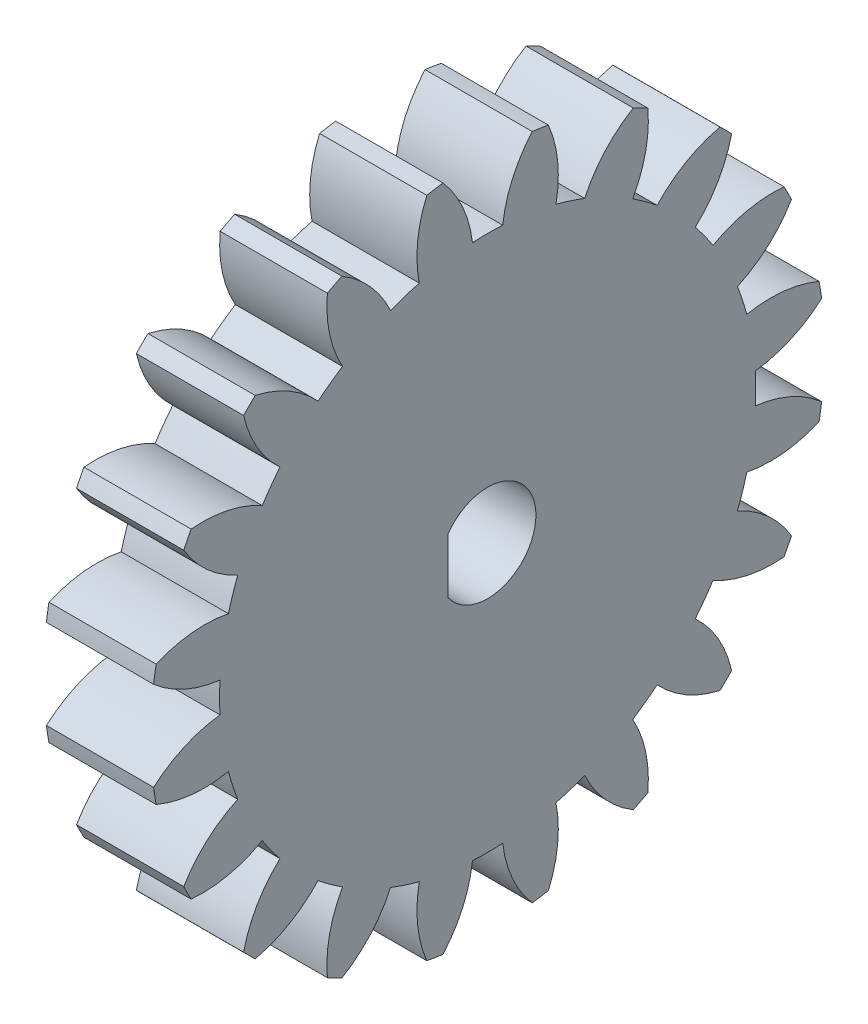
SolidWorks part; units mm, degrees
ref_plane "Plane1" through (0, 0, 0) normal (0, 0, 1) x (1, 0, 0)
ref_plane "Plane2" through (0, 0, 0) normal (0, 1, 0) x (1, 0, 0)
ref_plane "Plane3" through (0, 0, 0) normal (1, 0, 0) x (0, 0, -1)
other "Configuration Table"
sketch "HoldingSke" plane through (0, 0, 0) normal (0, 1, 0) x (1, 0, 0)
  line L0 (0, 0) -> (0.4698, -0.171)
  line L1 (-15, 0) -> (100, 0) construction
  line L2 (0, 0) -> (-2.1039, 2.3779)
  line L3 (0, 0) -> (-11.863, 4.5341)
  line L4 (0, 0) -> (8.1152, 2.9537)
  line L5 (0, 0) -> (-12.1804, -4.5429)
  line L6 (0, 0) -> (-5.8027, -3.9151)
  line L7 (-2.1039, 2.3779) -> (0.6944, 15.0732)
  line L8 (-76.2, 54.61) -> (-75.2, 54.61)
  line L9 (-71.009, 38.7566) -> (-53.1078, 45.2721)
  line L10 (-76.2, 71.12) -> (104.1128, 71.12)
  line L11 (0, 0) -> (-7, 0)
  line L12 (-76.2, 101.6) -> (-76.133, 101.6)
  line L13 (24.9733, 27.94) -> (52.9518, 28.4284)
  line L14 (24.9733, 27.94) -> (24.9743, 27.94)
  line L15 (24.9733, 27.94) -> (100.4006, 29.5858)
  line L16 (-63.627, -2) -> (-12.827, -2)
  circle A0 centre (0, 0) radius 3
  circle A1 centre (0, 0) radius 5
  circle A2 centre (0, 0) radius 5
  circle A3 centre (0, 0) radius 3
  dimension "MHD" = 10
  dimension "Hub_dia" = 10
  dimension "Bore" = 6
  dimension "MBD" = 6
  dimension "Num_teeth" = 20
  dimension "Pitch" = 0.5
  dimension "Overall_len" = 13
  dimension "Show_teeth" = 20
  dimension "Thickness" = 7
  dimension "OAL" = 13.0001
  dimension "T_dim" = 1
  dimension "Ap" = 20
  dimension "H" = 19.05
  dimension "Pitch_radius" = 180.3128
  dimension "Width" = 7
  dimension "Backlash" = 0.067
  dimension "Addendum_fac" = 1
  dimension "Dedendum_fac" = 1.25
  dimension "Clearance_fac" = 0.25
  dimension "Dedendum_add" = 0.001
  dimension "Module" = 2
sketch "BasProSke" plane through (0, 0, 0) normal (0, 1, 0) x (1, 0, 0)
  line L0 (-10, 0) -> (60, 0) construction
  line L1 (0, 0) -> (0, 22)
  line L2 (0, 0) -> (7, 0)
  line L3 (7, 0) -> (7, 22)
  line L4 (7, 22) -> (0, 22)
  dimension "Thickness" = 7
  dimension "Diameter" = 44
revolve "Base-Revolve" add sketch "BasProSke" angle 360 about L0
sketch "TooCutSke" plane through (0, 0, 0) normal (1, 0, 0) x (0, 0, -1)
  line L1 (0, 0) -> (0, 107) construction
  line L2 (0, 0) -> (-1.6864, 19.9288) construction
  line L3 (0, 0) -> (-6.2409, 39.4033) construction
  line L4 (-1.6864, 19.9288) -> (-3.1204, 19.7016) construction
  arc A0 (0.9862, 17.4712) -> (-0.9862, 17.4712) centre (0, 0) ccw
  arc A1 (2.9329, 21.8293) -> (-2.9329, 21.8293) centre (0, 0) ccw
  circle A2 centre (0, 0) radius 20 construction
  circle A3 centre (0, 0) radius 18.7939 construction
  arc A4 (-0.9862, 17.4712) -> (-2.9329, 21.8293) centre (-8.9313, 16.536) ccw
  arc A5 (2.9329, 21.8293) -> (0.9862, 17.4712) centre (8.9313, 16.536) ccw
  dimension "Root_dia" = 34.998
  dimension "Overcut_dia" = 44.0508
  dimension "Pitch_dia" = 40
  dimension "Base_dia" = 37.5877
  dimension "Flank_rad" = 8
  dimension "Half_ang" = 9
  dimension "Half_CT" = 1.4519
extrude "ToothCut" cut sketch "TooCutSke" along normal through all
fillet "Breaks" [suppressed] radius 0.04
fillet "RootFillets" [suppressed] radius 0.501
pattern_circular "TeethCuts" count 20 every 18 about axis through (-10, 0, 0) along (1, 0, 0) of "ToothCut", "RootFillets", "Breaks"
sketch "HubNeaOneSke" plane through (0, 0, 0) normal (-1, 0, 0) x (0, 0, 1)
  circle A0 centre (0, 0) radius 7
  dimension "Diameter" = 14
extrude "HubNearOne" add sketch "HubNeaOneSke" along normal blind 6.0001
sketch "HubNeaBotSke" plane through (0, 0, 0) normal (-1, 0, 0) x (0, 0, 1)
  circle A0 centre (0, 0) radius 5
  dimension "Diameter" = 10
extrude "HubNearBoth" [suppressed] add sketch "HubNeaBotSke" along normal blind 3
ref_plane "FarPln" through (7, 0, 0) normal (1, 0, 0) x (0, 0, -1)
sketch "HubFarSke" plane through (7, 0, 0) normal (1, 0, 0) x (0, 0, -1)
  circle A0 centre (0, 0) radius 5
  dimension "Diameter" = 10
extrude "HubFar" [suppressed] add sketch "HubFarSke" along normal blind 3
sketch "BorSke" plane through (0, 0, 0) normal (1, 0, 0) x (0, 0, -1)
  circle A0 centre (0, 0) radius 3
  dimension "Diameter" = 6
extrude "Bore" cut sketch "BorSke" along normal mid plane 26.0001
sketch "KeySke" plane through (0, 0, 0) normal (1, 0, 0) x (0, 0, -1)
  line L0 (-1, 0) -> (-1, 4)
  line L1 (-1, 4) -> (1, 4)
  line L2 (1, 4) -> (1, 0)
  line L3 (0, 0) -> (0, 34) construction
  line L4 (-1, 0) -> (1, 0)
  dimension "Offset" = 4
  dimension "Width" = 2
extrude "Keyway" [suppressed] cut sketch "KeySke" along normal mid plane 26.0001
pattern_circular "Keyway2" [suppressed] count 2 every 90 about axis through (-10, 0, 0) along (1, 0, 0)
sketch "草图1" plane through (-6.0001, 0, 0) normal (-1, 0, 0) x (0, 0, 1)
  line L0 (2.6, 1.7783) -> (2.6, -1.7783)
  arc A0 (2.6, -1.7783) -> (2.6, 1.7783) centre (0, 0) ccw
  dimension "D2" = 6.3
  dimension "D1" = 2.6
sketch "草图2" plane through (0, 0, 0) normal (0, 0, 1) x (1, 0, 0)
  line L0 (-6.0001, 1.7783) -> (-6.0001, -1.7783) construction
  line L1 (-10.0322, 0) -> (1.9288, 0) construction
  circle A0 centre (-3.5001, 0) radius 1.65
  dimension "D1" = 3.3
  dimension "D2" = 2.5
sketch "草图4" plane through (-6.0001, 0, 0) normal (-1, 0, 0) x (0, 0, 1)
  circle A0 centre (0, 0) radius 3.15
  dimension "D1" = 6.3
extrude "切除-拉伸3" cut sketch "草图4" against normal through all both and the other way through all
extrude "凸台-拉伸1" add sketch "草图1" against normal through all
extrude "切除-拉伸4" cut sketch "草图2" against normal through all both and the other way through all
ref_plane "基准面1" through (0, 0, -7) normal (0, 0, 1) x (1, 0, 0)
sketch "草图5" plane through (0, 0, -7) normal (0, 0, 1) x (1, 0, 0)
  line L1 (-6.3823, 1.7047) -> (-6.4175, -1.6438)
  line L2 (-6.4175, -1.6438) -> (-3.5352, -3.3484)
  line L3 (-3.5352, -3.3484) -> (-0.6178, -1.7047)
  line L4 (-0.6178, -1.7047) -> (-0.5826, 1.6438)
  line L5 (-0.5826, 1.6438) -> (-3.4649, 3.3484)
  line L6 (-3.4649, 3.3484) -> (-6.3823, 1.7047)
  circle A0 centre (-3.5001, 0) radius 2.9 construction
  dimension "D1" = 5.8
extrude "切除-拉伸5" cut sketch "草图5" along normal blind 2
equation "' \"Module@HoldingSke\" = 6.35"
equation "' \"Num_teeth@HoldingSke\" = 12"
equation "' \"Ap@HoldingSke\" =  20"
equation "' \"Ap@HoldingSke\" = 20"
equation "' \"Width@HoldingSke\" = 0.5 * 25.4"
equation "' \"Hub_dia@HoldingSke\"= 1 * 25.4"
equation "' \"Hub_dia@HoldingSke\" = 1 * 25.4"
equation "' \"Overall_len@HoldingSke\" = 1.0 * 25.4"
equation "' \"Bore@HoldingSke\" = 0.75 * 25.4"
equation "' \"T_dim@HoldingSke\" = 0.1 * 25.4"
equation "' \"Width@KeySke\" = 0.25 * 25.4"
equation "' \"Show_teeth@HoldingSke\" = 13"
equation "' \"Backlash@HoldingSke\" = 0.009 * 25.4"
equation "' \"Addendum_fac@HoldingSke\" = 1.0"
equation "' \"Dedendum_fac@HoldingSke\" = 1.25"
equation "' \"Dedendum_add@HoldingSke\" = 0.00005 * 25.4"
equation "' \"Clearance_fac@HoldingSke\" = 0.25"
equation "\"Pitch@HoldingSke\" = 1 / \"Module@HoldingSke\""
equation "\"Overcut_dia@TooCutSke\" = (\"Num_teeth@HoldingSke\" + 2 * \"Addendum_fac@HoldingSke\") / \"Pitch@HoldingSke\" + 0.002 * 25.4"
equation "\"Pitch_dia@TooCutSke\" = \"Num_teeth@HoldingSke\" / \"Pitch@HoldingSke\""
equation "\"Base_dia@TooCutSke\" = \"Num_teeth@HoldingSke\" / \"Pitch@HoldingSke\" * cos((\"Ap@HoldingSke\"  * 3.14159265 / 180))"
equation "\"Root_dia@TooCutSke\" = (\"Num_teeth@HoldingSke\" + 2) / \"Pitch@HoldingSke\" - 2 * (\"Addendum_fac@HoldingSke\" + \"Dedendum_fac@HoldingSke\") / \"Pitch@HoldingSke\" - \"Dedendum_add@HoldingSke\" * 2"
equation "\"Half_ang@TooCutSke\" = 180 / \"Num_teeth@HoldingSke\""
equation "\"Half_CT@TooCutSke\" = \"Num_teeth@HoldingSke\" / \"Pitch@HoldingSke\" * sin((3.14159265 / 2 / \"Num_teeth@HoldingSke\")) / 2 - 7 * \"Backlash@HoldingSke\" / 4"
equation "\"Flank_rad@TooCutSke\" = \"Num_teeth@HoldingSke\" / \"Pitch@HoldingSke\" / 5"
equation "\"Radius@RootFillets\" = \"Clearance_fac@HoldingSke\" / \"Pitch@HoldingSke\" + \"Dedendum_add@HoldingSke\""
equation "\"Break_rad@Breaks\" = 0.02 / \"Pitch@HoldingSke\""
equation "\"Thickness@HoldingSke\" = \"Width@HoldingSke\""
equation "\"OAL@HoldingSke\" = \"Thickness@HoldingSke\""
equation "\"MHD@HoldingSke\" = (\"Num_teeth@HoldingSke\" + 2) / \"Pitch@HoldingSke\" - 2 * (\"Addendum_fac@HoldingSke\" + \"Dedendum_fac@HoldingSke\")  / \"Pitch@HoldingSke\" - \"Dedendum_add@HoldingSke\" * 2"
equation "\"MBD@HoldingSke\" = (\"Num_teeth@HoldingSke\" + 2) / \"Pitch@HoldingSke\" - 2 * (\"Addendum_fac@HoldingSke\" + \"Dedendum_fac@HoldingSke\")  / \"Pitch@HoldingSke\" - \"Dedendum_add@HoldingSke\" * 2 - 0.002 * 25.4"
equation "\"MHD@HoldingSke\" = ((sgn( \"MHD@HoldingSke\" - \"Hub_dia@HoldingSke\" )-1)*( \"MHD@HoldingSke\" - \"Hub_dia@HoldingSke\" ))/-2+ \"Hub_dia@HoldingSke\""
equation "\"MBD@HoldingSke\" = ((sgn( \"MBD@HoldingSke\" - \"Bore@HoldingSke\" )-1)*( \"MBD@HoldingSke\" - \"Bore@HoldingSke\" ))/-2+ \"Bore@HoldingSke\""
equation "\"OAL@HoldingSke\" = ((sgn( \"OAL@HoldingSke\" - \"Overall_len@HoldingSke\" )+1)*( \"OAL@HoldingSke\" - \"Overall_len@HoldingSke\" ))/2 + \"Overall_len@HoldingSke\" + 0.000002 * 25.4"
equation "\"Num_teeth@TeethCuts\" = int( \"Show_teeth@HoldingSke\" ) + 1"
equation "\"Num_teeth@TeethCuts\" = ((sgn( \"Num_teeth@TeethCuts\" - \"Num_teeth@HoldingSke\" )-1)*( \"Num_teeth@TeethCuts\" - \"Num_teeth@HoldingSke\" ))/-2+ \"Num_teeth@HoldingSke\""
equation "\"Num_teeth@TeethCuts\" = ((sgn( \"Num_teeth@TeethCuts\" - 2.0)+1)*( \"Num_teeth@TeethCuts\" - 2.0))/2 +2.0"
equation "\"Angle@TeethCuts\" = 360.0 / \"Num_teeth@HoldingSke\""
equation "\"Diameter@BasProSke\" = (\"Num_teeth@HoldingSke\" + 2 * \"Addendum_fac@HoldingSke\") / \"Pitch@HoldingSke\""
equation "\"Thickness@BasProSke\"  = \"Thickness@HoldingSke\""
equation "' \"Fillet_rad@BasProSke\" =  \"Thickness@HoldingSke\" * 0.05"
equation "' \"Fillet_rad@BasProSke\" = \"Thickness@HoldingSke\" * 0.05"
equation "\"MHD@HoldingSke\" = ((sgn( \"MHD@HoldingSke\" - \"Root_dia@TooCutSke\" )-1)*( \"MHD@HoldingSke\" - \"Root_dia@TooCutSke\" ))/-2+ \"Root_dia@TooCutSke\""
equation "\"Diameter@HubNeaOneSke\"=14"
equation "\"Length@HubNearOne\" = \"OAL@HoldingSke\" - \"Thickness@BasProSke\""
equation "\"Diameter@HubNeaBotSke\" = \"MHD@HoldingSke\""
equation "\"Length@HubNearBoth\" = ( \"OAL@HoldingSke\" - \"Thickness@BasProSke\" ) / 2.0"
equation "\"Thickness@FarPln\" = \"Thickness@BasProSke\""
equation "\"Diameter@HubFarSke\" = \"MHD@HoldingSke\""
equation "\"Length@HubFar\" = ( \"OAL@HoldingSke\" - \"Thickness@BasProSke\" ) / 2.0"
equation "\"Diameter@BorSke\" = \"MBD@HoldingSke\""
equation "\"D1@Bore\" = \"OAL@HoldingSke\" * 2.0"
equation "\"D1@Keyway\" = \"OAL@HoldingSke\" * 2.0"
equation "\"Offset@KeySke\" = \"T_dim@HoldingSke\" + \"MBD@HoldingSke\" / 2.0"
